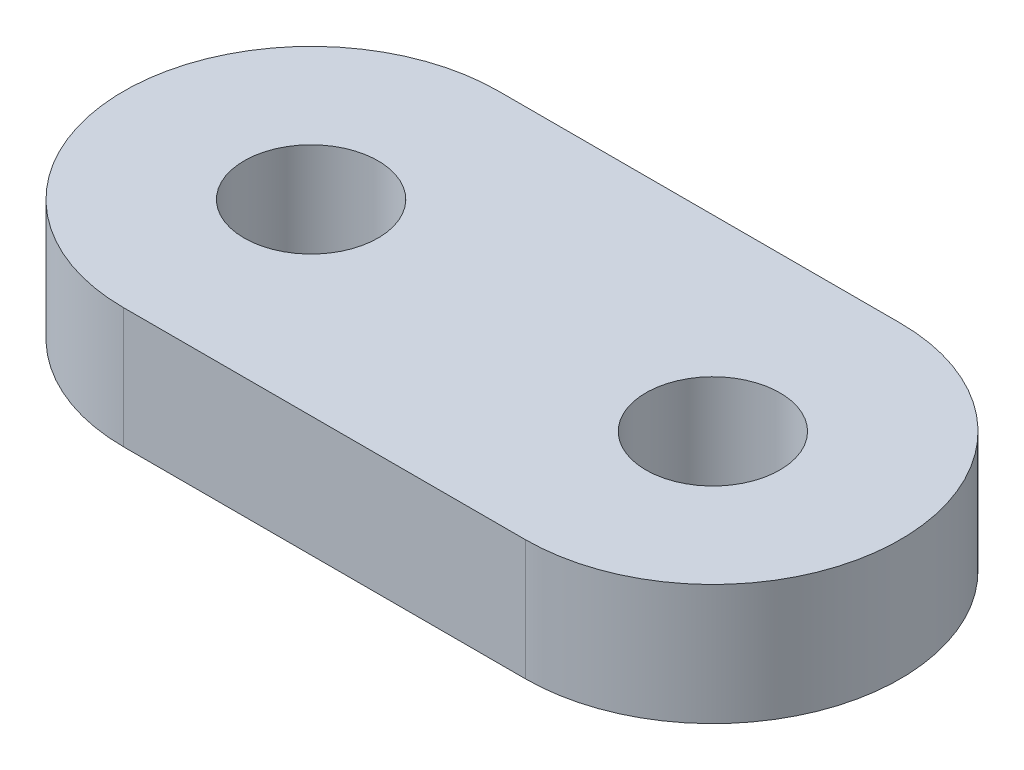
SolidWorks part; units mm, degrees
ref_plane "Спереди" through (0, 0, 0) normal (0, 0, 1) x (1, 0, 0)
ref_plane "Сверху" through (0, 0, 0) normal (0, 1, 0) x (1, 0, 0)
ref_plane "Справа" through (0, 0, 0) normal (1, 0, 0) x (0, 0, -1)
sketch "Эскиз1" plane through (0, 0, 0) normal (0, 1, 0) x (1, 0, 0)
  line L1 (15, 7) -> (30, 7)
  line L2 (15, -7) -> (30, -7)
  circle A0 centre (15, 0) radius 2.5
  arc A1 (15, 7) -> (15, -7) centre (15, 0) ccw
  circle A2 centre (30, 0) radius 2.5
  arc A3 (30, -7) -> (30, 7) centre (30, 0) ccw
  dimension "D1" = 15
  dimension "D2" = 7
extrude "Вытянуть1" add sketch "Эскиз1" along normal blind 4.5
